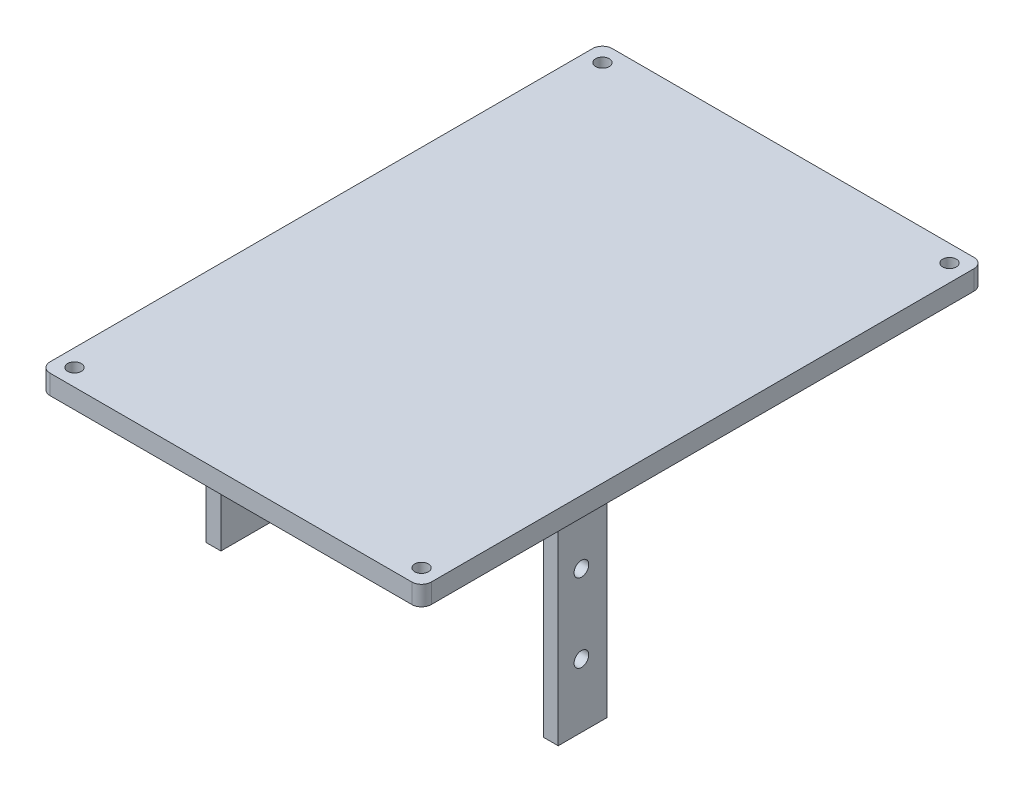
SolidWorks part; units mm, degrees
ref_plane "Front Plane" through (0, 0, 0) normal (0, 0, 1) x (1, 0, 0)
ref_plane "Top Plane" through (0, 0, 0) normal (0, 1, 0) x (1, 0, 0)
ref_plane "Right Plane" through (0, 0, 0) normal (1, 0, 0) x (0, 0, -1)
sketch "Sketch1" plane through (0, 0, 0) normal (0, 1, 0) x (1, 0, 0)
  line L1 (39, -57.5) -> (-39, -57.5)
  line L2 (39, -57.5) -> (39, 57.5)
  line L3 (39, 57.5) -> (-39, 57.5)
  line L4 (-39, -57.5) -> (-39, 57.5)
  line L5 (39, -57.5) -> (-39, 57.5) construction
  line L6 (39, 57.5) -> (-39, -57.5) construction
  point P0 (0, 0)
  dimension "D1" = 78
  dimension "D2" = 115
extrude "Boss-Extrude1" add sketch "Sketch1" along normal blind 4
sketch "Sketch5" plane through (0, 4, 0) normal (0, 1, 0) x (1, 0, 0)
  line L0 (-39, 57.5) -> (-39, -57.5) construction
  line L1 (39, 57.5) -> (-39, 57.5) construction
  line L2 (39, -57.5) -> (39, 57.5) construction
  line L3 (0, 0) -> (63.28, 0) construction
  circle A0 centre (-35.5, 54) radius 1.4
  circle A1 centre (35.5, 54) radius 1.4
  circle A2 centre (35.5, -54) radius 1.4
  circle A3 centre (-35.5, -54) radius 1.4
  dimension "D1" = 2.8
  dimension "D2" = 3.5
  dimension "D3" = 3.5
  dimension "D4" = 2.8
  dimension "D5" = 3.5
  dimension "D6" = 3.5
extrude "Cut-Extrude3" cut sketch "Sketch5" against normal blind 2
sketch "Sketch6" plane through (0, 0, 0) normal (0, -1, 0) x (1, 0, 0)
  line L0 (-39, 57.5) -> (39, 57.5) construction
  line L1 (-36, 26.55) -> (-33, 26.55)
  line L2 (-36, 26.55) -> (-36, 16.55)
  line L3 (-36, 16.55) -> (-33, 16.55)
  line L4 (-33, 26.55) -> (-33, 16.55)
  line L5 (-39, -57.5) -> (-39, 57.5) construction
  line L6 (0, 0) -> (0, 34.8993) construction
  line L7 (33, 26.55) -> (33, 16.55)
  line L8 (36, 16.55) -> (33, 16.55)
  line L9 (36, 26.55) -> (36, 16.55)
  line L10 (36, 26.55) -> (33, 26.55)
  point P4 (-34.5, 16.55)
  dimension "D1" = 10
  dimension "D2" = 3
  dimension "D3" = 30.95
  dimension "D4" = 3
extrude "Boss-Extrude3" add sketch "Sketch6" along normal blind 41
sketch "Sketch7" plane through (36, 0, 0) normal (1, 0, 0) x (0, 0, -1)
  line L0 (-26.55, -41) -> (-26.55, 0) construction
  line L1 (-57.5, 0) -> (57.5, 0) construction
  circle A0 centre (-21.8, -12) radius 1.5
  circle A2 centre (-21.8, -28) radius 1.5
  dimension "D1" = 3
  dimension "D2" = 4.75
  dimension "D3" = 12
  dimension "D4" = 3
  dimension "D5" = 16
  dimension "D6" = 4.75
extrude "Cut-Extrude4" cut sketch "Sketch7" against normal through all
fillet "Fillet1" radius 2 4 edges at (-39, 2, -57.5) (-39, 2, 57.5) (39, 2, 57.5) (39, 2, -57.5)
